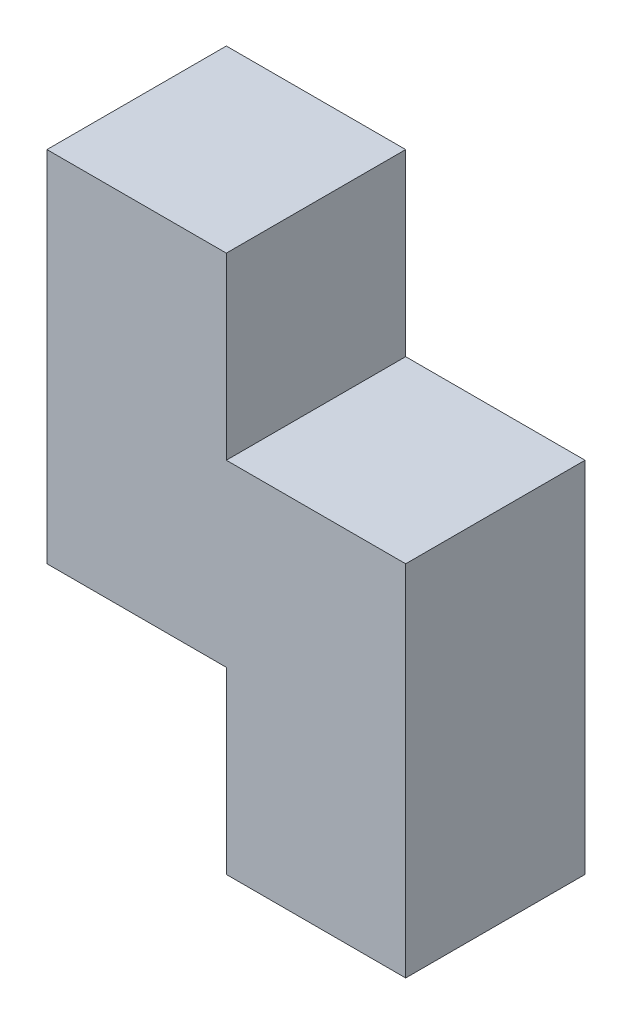
SolidWorks part; units mm, degrees
ref_plane "Front Plane" through (0, 0, 0) normal (1, 0, 0) x (0, 1, 0)
ref_plane "Top Plane" through (0, 0, 0) normal (0, 0, 1) x (0, 1, 0)
ref_plane "Right Plane" through (0, 0, 0) normal (0, 1, 0) x (-1, 0, 0)
sketch "Sketch1" plane through (0, 0, 0) normal (0, 0, 1) x (0, 1, 0)
  line L1 (-45, -30) -> (45, -30)
  line L2 (-45, -30) -> (-45, 30)
  line L3 (-45, 30) -> (45, 30)
  line L4 (45, -30) -> (45, 30)
  line L5 (-45, -30) -> (45, 30) construction
  line L6 (-45, 30) -> (45, -30) construction
  point P0 (0, 0)
  dimension "D1" = 90
  dimension "D2" = 60
extrude "Boss-Extrude1" add sketch "Sketch1" along normal mid plane 30
sketch "Sketch2" plane through (0, 0, 15) normal (0, 0, 1) x (1, 0, 0)
  line L0 (0, -15) -> (-30, -15)
  line L4 (0, -45) -> (0, -15)
  line L5 (-30, -45) -> (30, -45) construction
  line L6 (0, 45) -> (0, 15)
  line L7 (30, 45) -> (-30, 45) construction
  line L8 (0, 15) -> (30, 15)
  line L9 (30, -45) -> (30, 45) construction
  line L10 (-30, 45) -> (-30, -45) construction
extrude "Cut-Extrude1" cut sketch "Sketch2" against normal through all
